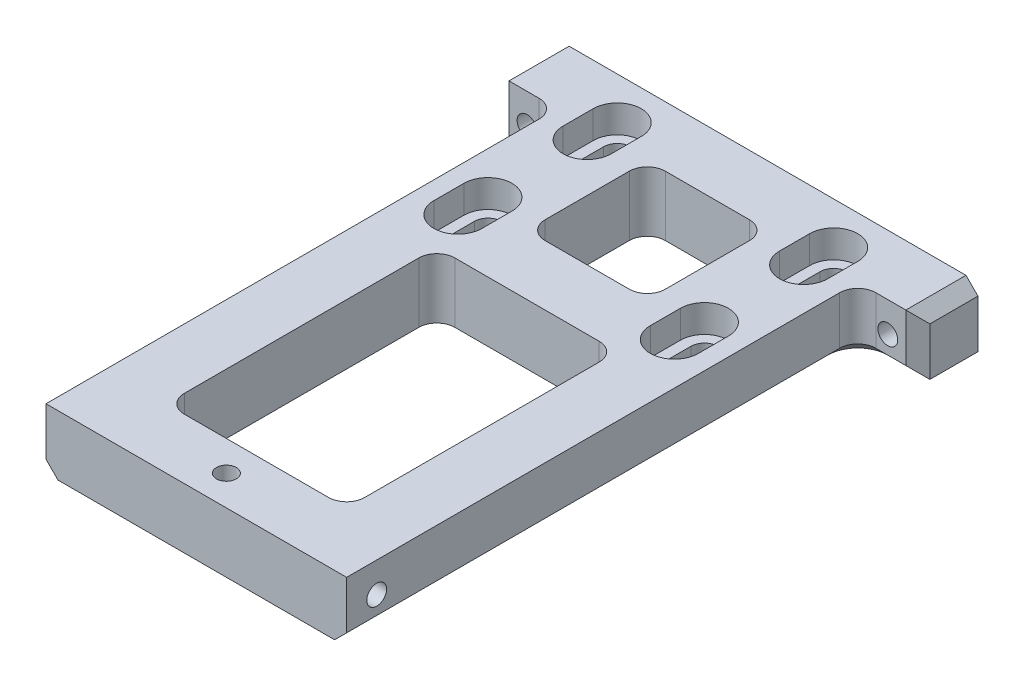
SolidWorks part; units mm, degrees
material "6061 Alloy"
ref_plane "Front Plane" through (0, 0, 0) normal (0, 0, 1) x (1, 0, 0)
ref_plane "Top Plane" through (0, 0, 0) normal (0, 1, 0) x (1, 0, 0)
ref_plane "Right Plane" through (0, 0, 0) normal (1, 0, 0) x (0, 0, -1)
sketch "Sketch1" plane through (0, 0, 0) normal (0, 1, 0) x (1, 0, 0)
  line L1 (35, -20.25) -> (-35, -20.25)
  line L2 (35, -20.25) -> (35, 20.25)
  line L3 (35, 20.25) -> (-35, 20.25)
  line L4 (-35, -20.25) -> (-35, 20.25)
  line L5 (35, -20.25) -> (-35, 20.25) construction
  line L6 (35, 20.25) -> (-35, -20.25) construction
  point P0 (0, 0)
  dimension "D1" = 70
  dimension "D2" = 40.5
extrude "Boss-Extrude1" add sketch "Sketch1" along normal mid plane 10
hole_wizard "CBORE for M4 Hexagon socket head cap screws1" positions "Sketch2" profile "Sketch3" counterbore size "M4" standard "GB" end condition through all
sketch "Sketch2" plane through (0, 5, 0) normal (0, 1, 0) x (1, 0, 0)
  line L0 (0, -55) -> (0, 55) construction
  line L1 (-55, 0) -> (55, 0) construction
  point P0 (-18, 10.75)
  point P5 (18, 10.75)
  point P8 (18, -10.75)
  point P9 (-18, -10.75)
  dimension "D1" = 36
  dimension "D2" = 21.5
sketch "Sketch3" plane through (-18, 5, -10.75) normal (1, 0, 0) x (0, 0, 1)
  line L0 (0, 0) -> (0, 10)
  line L1 (0, 10) -> (2.25, 10)
  line L3 (2.25, 10) -> (2.25, 4.6)
  line L4 (2.25, 4.6) -> (4, 4.6)
  line L5 (4, 4.6) -> (4, 0)
  line L7 (4, 0) -> (0, 0)
  line L11 (0, -6.35) -> (0, 107.95) construction
  dimension "Thru Hole Dia." = 4.5
  dimension "Thru Hole Depth" = 10
  dimension "C'Bore Dia." = 8
  dimension "C'Bore Depth" = 4.6
sketch "Sketch4" plane through (0, 0.4, 0) normal (0, 1, 0) x (1, 0, 0)
  line L0 (-18, 8.25) -> (-18, 13.25) construction
  line L1 (-22, 8.25) -> (-22, 13.25)
  line L2 (-14, 8.25) -> (-14, 13.25)
  line L3 (18, 13.25) -> (18, 8.25) construction
  line L4 (22, 13.25) -> (22, 8.25)
  line L5 (14, 13.25) -> (14, 8.25)
  line L6 (-18, -8.25) -> (-18, -13.25) construction
  line L7 (-14, -8.25) -> (-14, -13.25)
  line L8 (-22, -8.25) -> (-22, -13.25)
  line L9 (18, -8.25) -> (18, -13.25) construction
  line L10 (22, -8.25) -> (22, -13.25)
  line L11 (14, -8.25) -> (14, -13.25)
  arc A0 (-22, 8.25) -> (-14, 8.25) centre (-18, 8.25) ccw
  arc A1 (-14, 13.25) -> (-22, 13.25) centre (-18, 13.25) ccw
  circle A2 centre (-18, 10.75) radius 4 construction
  arc A3 (22, 13.25) -> (14, 13.25) centre (18, 13.25) ccw
  arc A4 (14, 8.25) -> (22, 8.25) centre (18, 8.25) ccw
  arc A5 (-14, -8.25) -> (-22, -8.25) centre (-18, -8.25) ccw
  arc A6 (-22, -13.25) -> (-14, -13.25) centre (-18, -13.25) ccw
  arc A7 (22, -8.25) -> (14, -8.25) centre (18, -8.25) ccw
  arc A8 (14, -13.25) -> (22, -13.25) centre (18, -13.25) ccw
  circle A10 centre (18, -10.75) radius 2.25 construction
  point P2 (-18, 10.75)
  point P12 (18, 10.75)
  point P19 (-18, -10.75)
  point P27 (18, -10.75)
  dimension "D1" = 5
extrude "Cut-Extrude1" cut sketch "Sketch4" along normal through all
sketch "Sketch5" plane through (0, 0.4, 0) normal (0, 1, 0) x (1, 0, 0)
  line L0 (-18, 13.25) -> (-18, 8.25) construction
  line L1 (-15.75, 13.25) -> (-15.75, 8.25)
  line L2 (-20.25, 13.25) -> (-20.25, 8.25)
  line L3 (18, 13.25) -> (18, 8.25) construction
  line L4 (20.25, 13.25) -> (20.25, 8.25)
  line L5 (15.75, 13.25) -> (15.75, 8.25)
  line L6 (-18, -8.25) -> (-18, -13.25) construction
  line L7 (-15.75, -8.25) -> (-15.75, -13.25)
  line L8 (-20.25, -8.25) -> (-20.25, -13.25)
  line L9 (18, -8.25) -> (18, -13.25) construction
  line L10 (20.25, -8.25) -> (20.25, -13.25)
  line L11 (15.75, -8.25) -> (15.75, -13.25)
  arc A0 (-15.75, 13.25) -> (-20.25, 13.25) centre (-18, 13.25) ccw
  arc A1 (-20.25, 8.25) -> (-15.75, 8.25) centre (-18, 8.25) ccw
  arc A2 (20.25, 13.25) -> (15.75, 13.25) centre (18, 13.25) ccw
  arc A3 (15.75, 8.25) -> (20.25, 8.25) centre (18, 8.25) ccw
  arc A4 (-15.75, -8.25) -> (-20.25, -8.25) centre (-18, -8.25) ccw
  arc A5 (-20.25, -13.25) -> (-15.75, -13.25) centre (-18, -13.25) ccw
  arc A6 (20.25, -8.25) -> (15.75, -8.25) centre (18, -8.25) ccw
  arc A7 (15.75, -13.25) -> (20.25, -13.25) centre (18, -13.25) ccw
  circle A8 centre (-18, 10.75) radius 2.25 construction
  arc A9 (-14, 13.25) -> (-22, 13.25) centre (-18, 13.25) ccw construction
  point P2 (-18, 10.75)
  point P9 (18, 10.75)
  point P17 (-18, -10.75)
  point P25 (18, -10.75)
extrude "Cut-Extrude2" cut sketch "Sketch5" against normal through all
sketch "Sketch6" plane through (0, 5, 0) normal (0, 1, 0) x (1, 0, 0)
  line L0 (-35, 20.25) -> (-35, -20.25) construction
  line L1 (-35, 20.25) -> (-45, 20.25)
  line L2 (-35, 20.25) -> (-35, 10.25)
  line L3 (-35, 10.25) -> (-45, 10.25)
  line L4 (-45, 20.25) -> (-45, 10.25)
  line L5 (0, -55) -> (0, 55) construction
  line L6 (45, 20.25) -> (45, 10.25)
  line L7 (35, 10.25) -> (45, 10.25)
  line L8 (35, 20.25) -> (35, 10.25)
  line L9 (35, 20.25) -> (45, 20.25)
  line L10 (35, 20.25) -> (-35, 20.25) construction
  dimension "D1" = 10
  dimension "D2" = 10
extrude "Boss-Extrude2" [suppressed] add sketch "Sketch6" against normal up to surface (10 mm away)
hole_wizard "M4 Tapped Hole1" positions "Sketch7" profile "Sketch9" tap size "M4" standard "GB" end condition through all
sketch "Sketch7" plane through (0, 0, -20.25) normal (0, 0, -1) x (-1, 0, 0)
  line L0 (0, 55) -> (0, -55) construction
  point P0 (-30, 0)
  point P10 (30, 0)
  dimension "D1" = 30
cosmetic thread "Hole Thread1" parameters "D2"=4
cosmetic thread "Hole Thread2" parameters "D2"=4
sketch "Sketch9" plane through (30, 0, -20.25) normal (1, 0, 0) x (0, 1, 0)
  line L0 (0, 0) -> (0, 40.5)
  line L1 (0, 40.5) -> (1.65, 40.5)
  line L2 (1.65, 40.5) -> (1.65, 0)
  line L5 (1.65, 0) -> (0, 0)
  line L11 (0, -6.35) -> (0, 107.95) construction
  dimension "Thru Tap Drill Dia." = 3.3
  dimension "Thru Tap Drill Depth" = 40.5
sketch "Sketch10" plane through (0, 5, 0) normal (0, 1, 0) x (1, 0, 0)
  line L0 (-35, 20.25) -> (-35, -20.25) construction
  line L1 (-35, 10.25) -> (-25, 10.25)
  line L2 (-35, 10.25) -> (-35, -20.25)
  line L3 (-35, -20.25) -> (-25, -20.25)
  line L4 (-25, 10.25) -> (-25, -20.25)
  line L5 (-35, -20.25) -> (35, -20.25) construction
  line L6 (35, 20.25) -> (-35, 20.25) construction
  line L7 (0, -55) -> (0, 55) construction
  line L8 (25, 10.25) -> (25, -20.25)
  line L9 (35, -20.25) -> (25, -20.25)
  line L10 (35, 10.25) -> (35, -20.25)
  line L11 (35, 10.25) -> (25, 10.25)
  dimension "D1" = 10
  dimension "D2" = 10
extrude "Cut-Extrude3" cut sketch "Sketch10" against normal through all
sketch "Sketch13" plane through (0, 5, 0) normal (0, 1, 0) x (1, 0, 0)
  line L0 (-25, -20.25) -> (-25, 10.25) construction
  line L1 (-25, -20.25) -> (25, -20.25)
  line L2 (-25, -20.25) -> (-25, -74.75)
  line L3 (-25, -74.75) -> (25, -74.75)
  line L4 (25, -20.25) -> (25, -74.75)
  line L5 (25, 10.25) -> (25, -20.25) construction
  line L6 (-25, -20.25) -> (25, -20.25) construction
  dimension "D1" = 54.5
extrude "Boss-Extrude3" add sketch "Sketch13" against normal up to surface (10 mm away) contours L2 L3 L4 L1 up to face at (-18, -5, -10.75)
sketch "Sketch14" plane through (0, 5, 0) normal (0, 1, 0) x (1, 0, 0)
  line L5 (-25, 10.25) -> (-35, 10.25) construction
  line L6 (10, -9.75) -> (-10, -9.75)
  line L7 (15, -19.75) -> (-15, -19.75)
  line L8 (15, -19.75) -> (15, -64.75)
  line L9 (15, -64.75) -> (-15, -64.75)
  line L10 (-15, -19.75) -> (-15, -64.75)
  line L11 (15, -19.75) -> (-15, -64.75) construction
  line L12 (15, -64.75) -> (-15, -19.75) construction
  line L13 (-25, -74.75) -> (-25, 10.25) construction
  line L14 (-25, -74.75) -> (25, -74.75) construction
  line L15 (10, -9.75) -> (10, 10.25)
  line L16 (10, 10.25) -> (-10, 10.25)
  line L17 (-10, -9.75) -> (-10, 10.25)
  line L18 (10, -9.75) -> (-10, 10.25) construction
  line L19 (10, 10.25) -> (-10, -9.75) construction
  point P0 (0, 0.25)
  point P5 (0, -42.25)
  dimension "D1" = 10
  dimension "D2" = 10
  dimension "D3" = 45
  dimension "D4" = 10
  dimension "D5" = 15
extrude "Cut-Extrude4" cut sketch "Sketch14" against normal through all contours L17 L6 L15 L16 | L7 L10 L9 L8
hole_wizard "M4 Tapped Hole2" positions "Sketch15" profile "Sketch17" tap size "M4" standard "GB"
sketch "Sketch15" plane through (-25, 0, 0) normal (-1, 0, 0) x (0, 0, 1)
  line L0 (74.75, -5) -> (74.75, 5) construction
  point P0 (69.75, 0)
  dimension "D1" = 5
sketch "Sketch17" plane through (-25, 0, 69.75) normal (0, 1, 0) x (0, 0, 1)
  line L0 (0, 0) -> (0, 12.4914)
  line L1 (0, 12.4914) -> (1.65, 11.5)
  line L2 (1.65, 11.5) -> (1.65, 0)
  line L5 (1.65, 0) -> (0, 0)
  line L10 (0, 12.4914) -> (-1.65, 11.5) construction
  line L11 (0, -6.35) -> (0, 107.95) construction
  dimension "Tap Drill Dia." = 3.3
  dimension "Tap Drill Depth" = 11.5
  dimension "Drill Angle" = 118
cosmetic thread "Hole Thread3" parameters "D1"=8, "D2"=4
mirror "Mirror1" about plane through (0, 0, 0) normal (1, 0, 0) of "M4 Tapped Hole2"
cosmetic thread "Hole Thread4" parameters "D1"=8, "D2"=4
hole_wizard "M4 Tapped Hole3" positions "Sketch18" profile "Sketch19" tap size "M4" standard "GB"
sketch "Sketch18" plane through (0, 5, 0) normal (0, 1, 0) x (1, 0, 0)
  line L0 (-25, -74.75) -> (25, -74.75) construction
  point P0 (0, -69.75)
  dimension "D1" = 5
sketch "Sketch19" plane through (0, 5, 69.75) normal (1, 0, 0) x (0, 0, 1)
  line L0 (0, 0) -> (0, 12.4914)
  line L1 (0, 12.4914) -> (1.65, 11.5)
  line L2 (1.65, 11.5) -> (1.65, 0)
  line L5 (1.65, 0) -> (0, 0)
  line L10 (0, 12.4914) -> (-1.65, 11.5) construction
  line L11 (0, -6.35) -> (0, 107.95) construction
  dimension "Tap Drill Dia." = 3.3
  dimension "Tap Drill Depth" = 11.5
  dimension "Drill Angle" = 118
cosmetic thread "Hole Thread5" parameters "D1"=8, "D2"=4
fillet "Fillet1" radius 3 10 edges at (25, 0, -10.25) (-25, 0, -10.25) (15, 0, 64.75) (-15, 0, 64.75) (15, 0, 19.75) (-15, 0, 19.75) (10, 0, -10.25) (10, 0, 9.75) (-10, 0, 9.75) (-10, 0, -10.25)
chamfer "Chamfer1" distance 2 angle 45 2 edges at (35, 0, -10.25) (-35, 0, -10.25)
chamfer "Chamfer2" distance 2 angle 45 2 edges at (35, 5, -16.25) (-35, 5, -16.25)
chamfer "Chamfer3" distance 2 angle 45 6 edges at (-30.5, -5, -10.25) (-25.8787, -5, -9.3713) (-25, -5, 33.75) (30.5, -5, -10.25) (25.8787, -5, -9.3713) (25, -5, 33.75)
